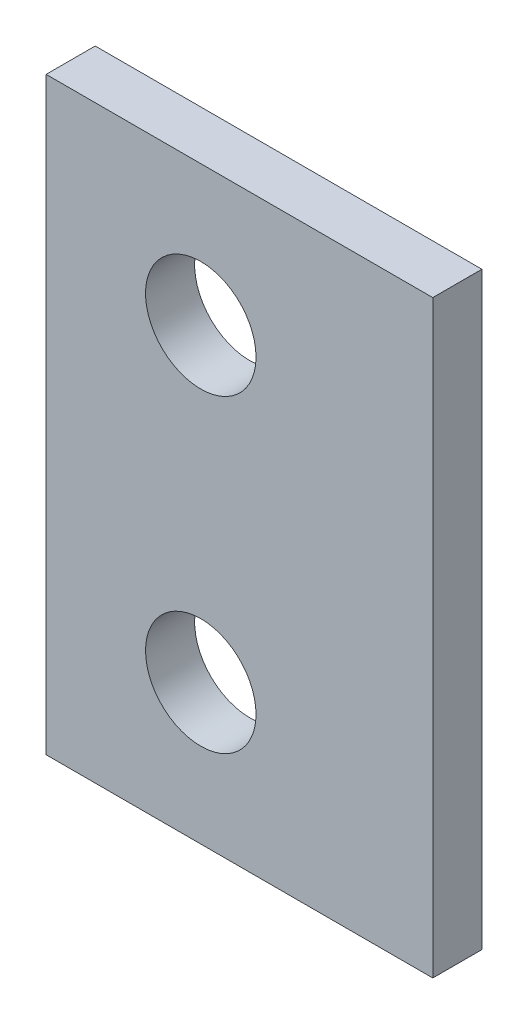
SolidWorks part; units mm, degrees
ref_plane "Alzado" through (0, 0, 0) normal (0, 0, 1) x (1, 0, 0)
ref_plane "Planta" through (0, 0, 0) normal (0, 1, 0) x (1, 0, 0)
ref_plane "Vista lateral" through (0, 0, 0) normal (1, 0, 0) x (0, 0, -1)
sketch "Croquis1" plane through (0, 0, 0) normal (0, 0, 1) x (1, 0, 0)
  line L1 (0, 0) -> (50, 0)
  line L2 (0, 0) -> (0, -76.2)
  line L3 (0, -76.2) -> (50, -76.2)
  line L4 (50, 0) -> (50, -76.2)
  dimension "D1" = 50
  dimension "D2" = 76.2
extrude "Saliente-Extruir1" add sketch "Croquis1" along normal blind 6.35
sketch "Croquis2" plane through (0, 0, 6.35) normal (0, 0, 1) x (1, 0, 0)
  line L0 (0, -38.1) -> (50, -38.1) construction
  line L1 (0, 0) -> (0, -76.2) construction
  line L2 (50, -76.2) -> (50, 0) construction
  line L3 (20, -38.1) -> (20, -18.1) construction
  circle A0 centre (20, -18.1) radius 7.1438
  circle A1 centre (20, -58.1) radius 7.1438
  dimension "D2" = 20
  dimension "D3" = 14.2875
  dimension "D1" = 20
extrude "Cortar-Extruir1" cut sketch "Croquis2" against normal blind 10
